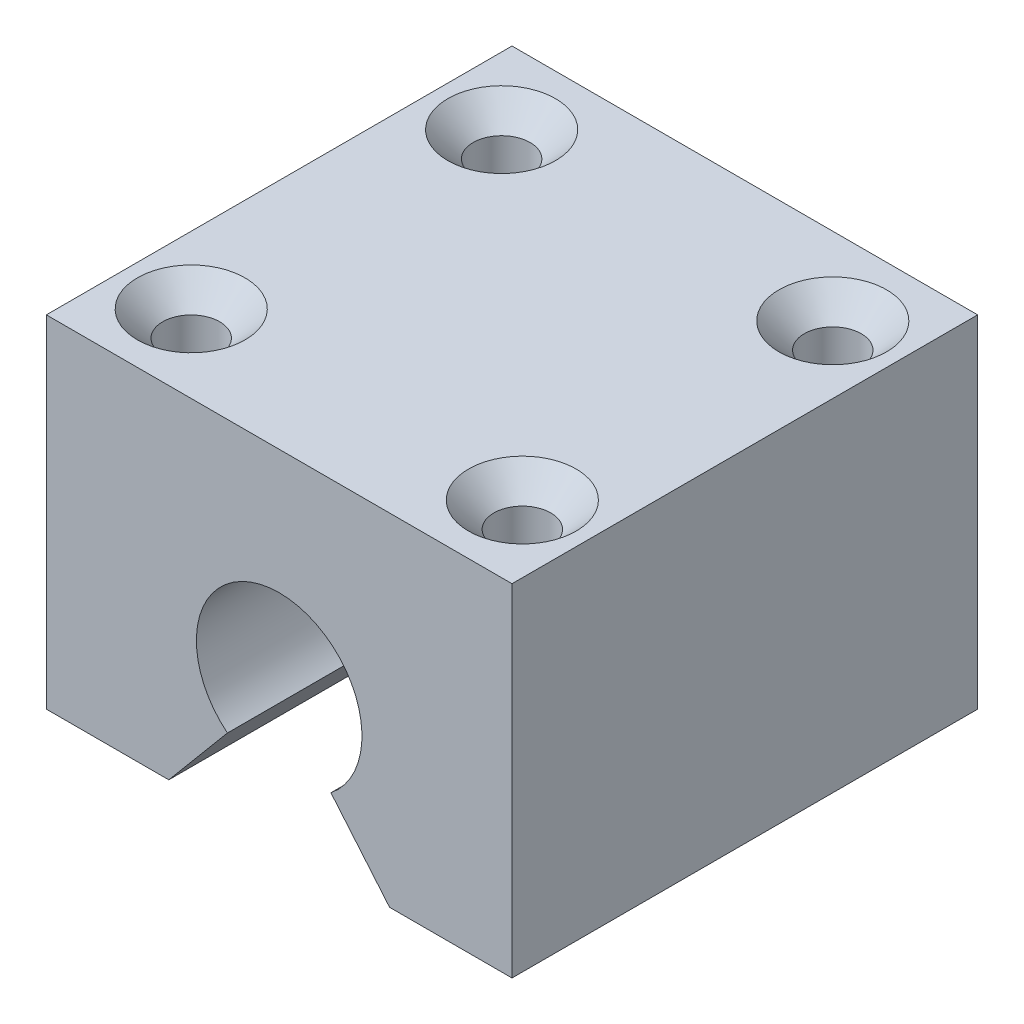
SolidWorks part; units mm, degrees
ref_plane "Front Plane" through (0, 0, 0) normal (0, 0, 1) x (1, 0, 0)
ref_plane "Top Plane" through (0, 0, 0) normal (0, 1, 0) x (1, 0, 0)
ref_plane "Right Plane" through (0, 0, 0) normal (1, 0, 0) x (0, 0, -1)
sketch "Sketch1" plane through (0, 0, 0) normal (0, 0, 1) x (1, 0, 0)
  line L1 (-22.5, 16.5) -> (22.5, 16.5)
  line L2 (-22.5, 16.5) -> (-22.5, -16.5)
  line L3 (-22.5, -16.5) -> (22.5, -16.5)
  line L4 (22.5, 16.5) -> (22.5, -16.5)
  line L5 (-22.5, 16.5) -> (22.5, -16.5) construction
  line L6 (-22.5, -16.5) -> (22.5, 16.5) construction
  point P0 (0, 0)
  dimension "D1" = 33
  dimension "D2" = 45
extrude "Boss-Extrude1" add sketch "Sketch1" along normal blind 45
sketch "Sketch2" plane through (0, 0, 45) normal (0, 0, 1) x (1, 0, 0)
  line L0 (22.5, 16.5) -> (-22.5, 16.5) construction
  line L1 (-22.5, -16.5) -> (22.5, -16.5) construction
  line L2 (-5, -9.745) -> (-10.6681, -16.5)
  line L3 (5, -9.745) -> (10.6681, -16.5)
  line L4 (0, -3.5) -> (0, -20.1929) construction
  line L5 (-10.6681, -16.5) -> (10.6681, -16.5)
  arc A0 (5, -9.745) -> (-5, -9.745) centre (0, -3.5) ccw
  dimension "D1" = 16
  dimension "D2" = 20
  dimension "D3" = 10
  dimension "D4" = 80
  dimension "D5" = 40
extrude "Cut-Extrude1" cut sketch "Sketch2" against normal blind 45
hole_wizard "CSK for M5 Countersunk Raised Head Screw1" positions "Sketch4" profile "Sketch3" countersink size "M5" standard "ISO"
sketch "Sketch4" plane through (0, 16.5, 0) normal (0, 1, 0) x (1, 0, 0)
  line L0 (22.5, -45) -> (22.5, 0) construction
  line L1 (-22.5, -45) -> (-22.5, 0) construction
  line L2 (22.5, -45) -> (-22.5, -45) construction
  point P0 (-16, -37.5)
  point P2 (-16, -7.5)
  point P4 (16, -7.5)
  point P6 (16, -37.5)
  dimension "D1" = 32
  dimension "D2" = 32
  dimension "D3" = 30
  dimension "D4" = 30
  dimension "D5" = 6.5
  dimension "D6" = 6.5
  dimension "D7" = 6.5
  dimension "D8" = 7.5
sketch "Sketch3" plane through (-16, 16.5, 37.5) normal (1, 0, 0) x (0, 0, 1)
  line L0 (0, 0) -> (0, 13.6524)
  line L1 (0, 13.6524) -> (2.75, 12)
  line L2 (2.75, 12) -> (2.75, 2.45)
  line L3 (2.75, 2.45) -> (5.2, 0)
  line L5 (5.2, 0) -> (0, 0)
  line L6 (-2.75, 2.45) -> (-5.2, 0) construction
  line L10 (0, 13.6524) -> (-2.75, 12) construction
  line L11 (0, -6.35) -> (0, 107.95) construction
  dimension "Hole Dia." = 5.5
  dimension "Hole Depth" = 12
  dimension "Near C'Sink Dia." = 10.4
  dimension "Near C'Sink Angle" = 90
  dimension "Drill Angle" = 118
